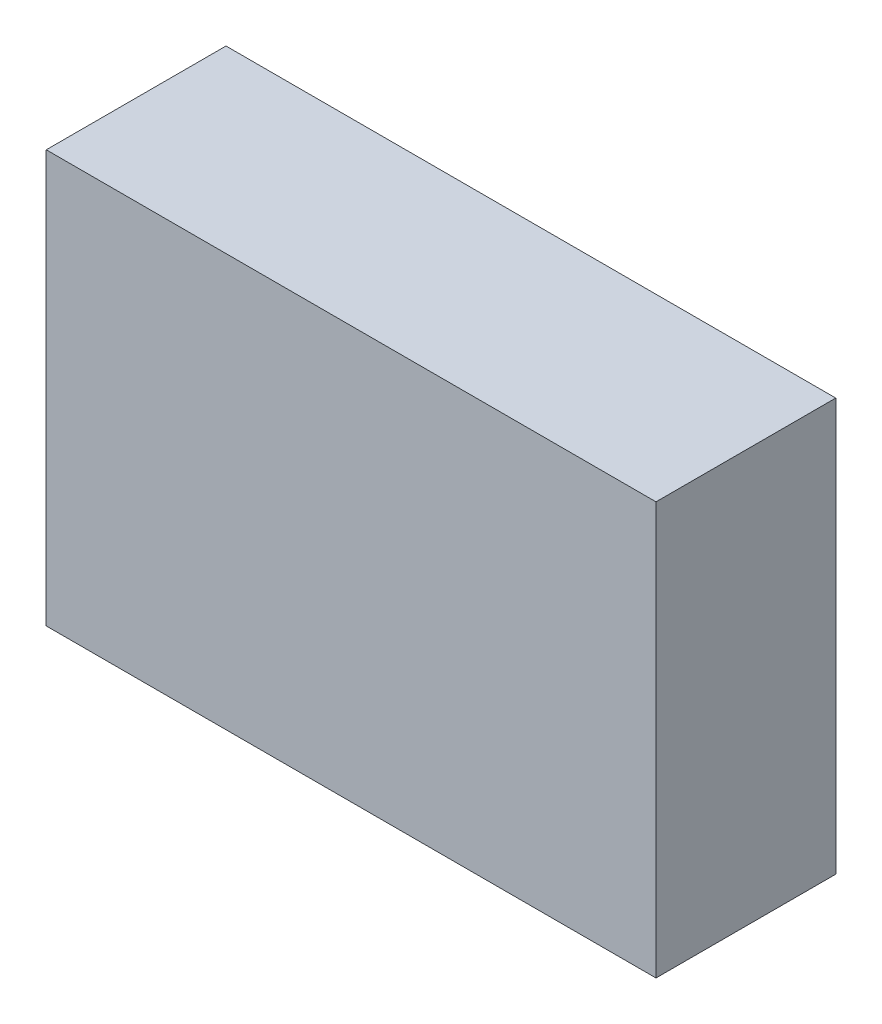
SolidWorks part; units mm, degrees
ref_plane "Front Plane" through (0, 0, 0) normal (0, 0, 1) x (1, 0, 0)
ref_plane "Top Plane" through (0, 0, 0) normal (0, 1, 0) x (1, 0, 0)
ref_plane "Right Plane" through (0, 0, 0) normal (1, 0, 0) x (0, 0, -1)
sketch "Sketch1" plane through (0, 0, 0) normal (0, 0, 1) x (1, 0, 0)
  line L1 (0, 0) -> (17.3, 0)
  line L2 (0, 0) -> (0, 11.7)
  line L3 (0, 11.7) -> (17.3, 11.7)
  line L4 (17.3, 0) -> (17.3, 11.7)
extrude "Boss-Extrude1" add sketch "Sketch1" along normal blind 5.1
